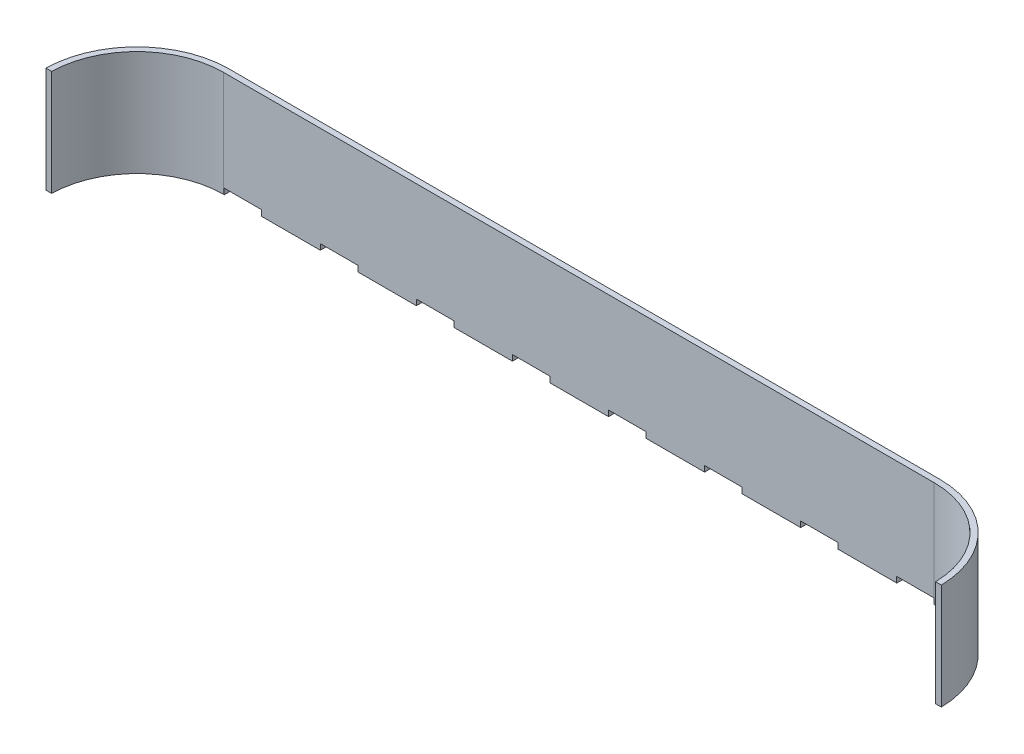
SolidWorks part; units mm, degrees
material "Oak"
ref_plane "Front Plane" through (0, 0, 0) normal (0, 0, 1) x (1, 0, 0)
ref_plane "Top Plane" through (0, 0, 0) normal (0, 1, 0) x (1, 0, 0)
ref_plane "Right Plane" through (0, 0, 0) normal (1, 0, 0) x (0, 0, -1)
sketch "Sketch1" plane through (0, 0, 0) normal (0, 1, 0) x (1, 0, 0)
  line L3 (-185, 0) -> (185, 0)
  line L9 (0, -30.3325) -> (0, 30.3325) construction
  line L11 (-185, 3) -> (185, 3)
  line L12 (-232.9944, -44.2685) -> (-229.9948, -44.3142)
  line L14 (229.9948, -44.3142) -> (232.9944, -44.2685)
  arc A4 (-185, 0) -> (-229.9948, -44.3142) centre (-185, -45) ccw
  arc A5 (185, 0) -> (229.9948, -44.3142) centre (185, -45) cw
  arc A6 (-185, 3) -> (-232.9944, -44.2685) centre (-185, -45) ccw
  arc A7 (185, 3) -> (232.9944, -44.2685) centre (185, -45) cw
  point P0 (0, 0)
  point P2 (0, 0)
  point P8 (0, 0)
  point P15 (0, 0)
  dimension "D1" = 45
  dimension "D2" = 70
  dimension "D3" = 3
  dimension "D5" = 370
extrude "Boss-Extrude4" add sketch "Sketch1" along normal mid plane 55
sketch "Sketch2" plane through (0, 0, -3) normal (0, 0, -1) x (-1, 0, 0)
  line L0 (-135, -27.5) -> (-115.5, -27.5)
  line L1 (-185, -27.5) -> (-165.5, -27.5)
  line L2 (-185, -27.5) -> (-185, -24.5)
  line L3 (-185, -24.5) -> (-165.5, -24.5)
  line L4 (-165.5, -27.5) -> (-165.5, -24.5)
  line L5 (-135, -27.5) -> (-135, -24.5)
  line L6 (-135, -24.5) -> (-115.5, -24.5)
  line L7 (-115.5, -27.5) -> (-115.5, -24.5)
  line L8 (-85, -27.5) -> (-65.5, -27.5)
  line L9 (-85, -27.5) -> (-85, -24.5)
  line L10 (-85, -24.5) -> (-65.5, -24.5)
  line L11 (-65.5, -27.5) -> (-65.5, -24.5)
  line L12 (-35, -27.5) -> (-15.5, -27.5)
  line L13 (-35, -27.5) -> (-35, -24.5)
  line L14 (-35, -24.5) -> (-15.5, -24.5)
  line L15 (-15.5, -27.5) -> (-15.5, -24.5)
  line L16 (15, -27.5) -> (34.5, -27.5)
  line L17 (15, -27.5) -> (15, -24.5)
  line L18 (15, -24.5) -> (34.5, -24.5)
  line L19 (34.5, -27.5) -> (34.5, -24.5)
  line L20 (65, -27.5) -> (84.5, -27.5)
  line L21 (65, -27.5) -> (65, -24.5)
  line L22 (65, -24.5) -> (84.5, -24.5)
  line L23 (84.5, -27.5) -> (84.5, -24.5)
  line L24 (115, -27.5) -> (134.5, -27.5)
  line L25 (115, -27.5) -> (115, -24.5)
  line L26 (115, -24.5) -> (134.5, -24.5)
  line L27 (134.5, -27.5) -> (134.5, -24.5)
  line L28 (165, -27.5) -> (184.5, -27.5)
  line L29 (165, -27.5) -> (165, -24.5)
  line L30 (165, -24.5) -> (184.5, -24.5)
  line L31 (184.5, -27.5) -> (184.5, -24.5)
  point P5 (0, 0)
  point P34 (0, 0)
  dimension "D1" = 19.5
  dimension "D2" = 3
  dimension "D3" = 8
extrude "Cut-Extrude1" cut sketch "Sketch2" against normal through all
